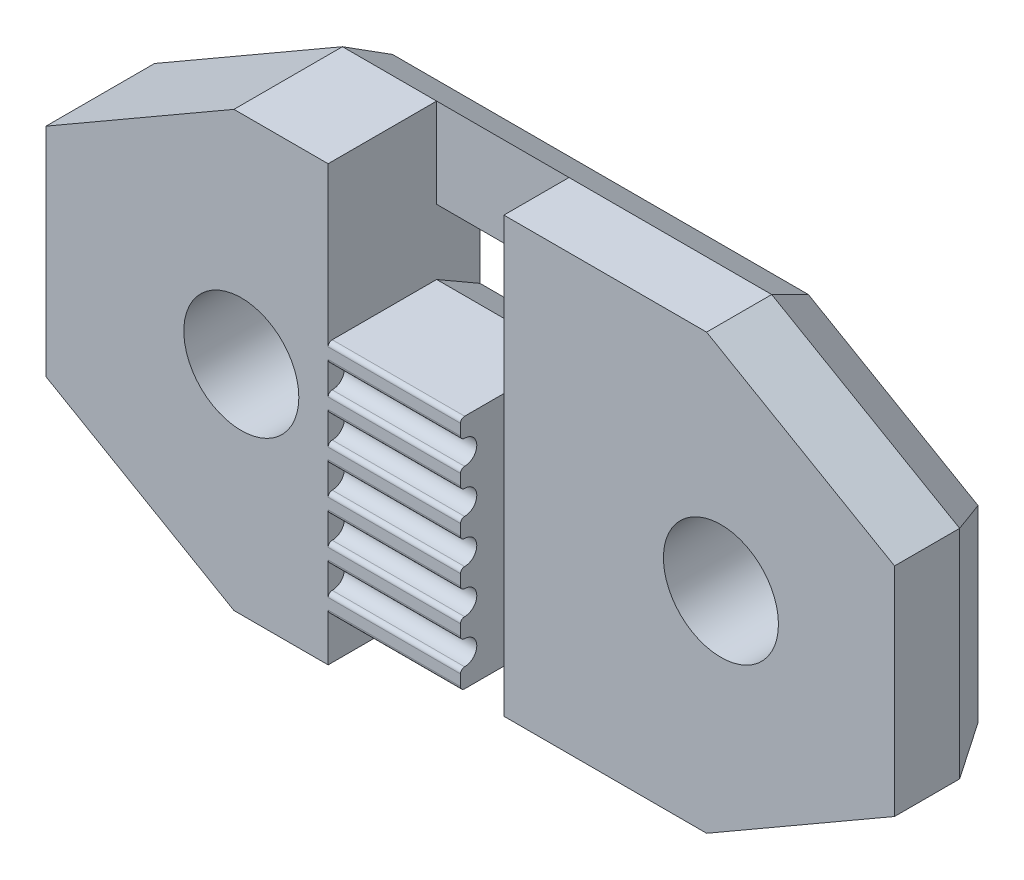
SolidWorks part; units mm, degrees
material "ABS"
ref_plane "Ebene vorne" through (0, 0, 0) normal (0, 0, 1) x (1, 0, 0)
ref_plane "Ebene oben" through (0, 0, 0) normal (0, 1, 0) x (1, 0, 0)
ref_plane "Ebene rechts" through (0, 0, 0) normal (1, 0, 0) x (0, 0, -1)
sketch "Skizze1" plane through (0, 0, 0) normal (0, 0, 1) x (1, 0, 0)
  line L0 (0, 0) -> (0, 9.44)
  line L1 (0, 9.44) -> (-7.24, 9.44) construction
  line L2 (-7.05, 10.19) -> (-7.05, 10.69)
  line L3 (-7.05, 8.69) -> (-7.05, 8.19)
  line L4 (-7.24, 10.88) -> (-9.24, 10.88)
  line L5 (-9.24, 10.88) -> (-9.24, 0)
  line L6 (-7.05, 6.69) -> (-7.05, 6.19)
  line L7 (-7.05, 4.69) -> (-7.05, 4.19)
  line L8 (-7.05, 2.69) -> (-7.05, 2.19)
  line L9 (-7.05, 0.69) -> (-7.05, 0.19)
  line L10 (-7.05, -1.31) -> (-7.05, -1.81) construction
  line L11 (-7.05, -3.31) -> (-7.05, -3.81) construction
  line L12 (-7.05, -5.31) -> (-7.05, -5.81) construction
  line L13 (-7.05, -7.31) -> (-7.05, -7.81) construction
  line L14 (-7.05, -9.31) -> (-7.05, -9.81) construction
  line L15 (-7.24, 0) -> (-9.24, 0)
  line L16 (0, 9.44) -> (0, 10.88)
  line L17 (0, 10.88) -> (-6, 10.88)
  line L18 (-6, 10.88) -> (-6, 0)
  line L19 (-6, 0) -> (0, 0)
  arc A0 (-7.24, 10) -> (-7.24, 8.88) centre (-7.24, 9.44) ccw
  arc A1 (-7.24, 8) -> (-7.24, 6.88) centre (-7.24, 7.44) ccw
  arc A2 (-7.05, 8.69) -> (-7.24, 8.88) centre (-7.24, 8.69) ccw
  arc A3 (-7.24, 8) -> (-7.05, 8.19) centre (-7.24, 8.19) ccw
  arc A4 (-7.05, 10.19) -> (-7.24, 10) centre (-7.24, 10.19) cw
  arc A5 (-7.24, 10.88) -> (-7.05, 10.69) centre (-7.24, 10.69) cw
  arc A6 (-7.24, 8) -> (-7.24, 6.88) centre (-7.24, 7.44) ccw
  arc A7 (-7.05, 6.69) -> (-7.24, 6.88) centre (-7.24, 6.69) ccw
  arc A8 (-7.24, 6) -> (-7.05, 6.19) centre (-7.24, 6.19) ccw
  arc A9 (-7.24, 6) -> (-7.24, 4.88) centre (-7.24, 5.44) ccw
  arc A10 (-7.05, 4.69) -> (-7.24, 4.88) centre (-7.24, 4.69) ccw
  arc A11 (-7.24, 4) -> (-7.05, 4.19) centre (-7.24, 4.19) ccw
  arc A12 (-7.24, 4) -> (-7.24, 2.88) centre (-7.24, 3.44) ccw
  arc A13 (-7.05, 2.69) -> (-7.24, 2.88) centre (-7.24, 2.69) ccw
  arc A14 (-7.24, 2) -> (-7.05, 2.19) centre (-7.24, 2.19) ccw
  arc A15 (-7.24, 2) -> (-7.24, 0.88) centre (-7.24, 1.44) ccw
  arc A16 (-7.05, 0.69) -> (-7.24, 0.88) centre (-7.24, 0.69) ccw
  arc A17 (-7.24, 0) -> (-7.05, 0.19) centre (-7.24, 0.19) ccw
  arc A18 (-7.24, 0) -> (-7.24, -1.12) centre (-7.24, -0.56) ccw construction
  arc A19 (-7.05, -1.31) -> (-7.24, -1.12) centre (-7.24, -1.31) ccw construction
  arc A20 (-7.24, -2) -> (-7.05, -1.81) centre (-7.24, -1.81) ccw construction
  arc A21 (-7.24, -2) -> (-7.24, -3.12) centre (-7.24, -2.56) ccw construction
  arc A22 (-7.05, -3.31) -> (-7.24, -3.12) centre (-7.24, -3.31) ccw construction
  arc A23 (-7.24, -4) -> (-7.05, -3.81) centre (-7.24, -3.81) ccw construction
  arc A24 (-7.24, -4) -> (-7.24, -5.12) centre (-7.24, -4.56) ccw construction
  arc A25 (-7.05, -5.31) -> (-7.24, -5.12) centre (-7.24, -5.31) ccw construction
  arc A26 (-7.24, -6) -> (-7.05, -5.81) centre (-7.24, -5.81) ccw construction
  arc A27 (-7.24, -6) -> (-7.24, -7.12) centre (-7.24, -6.56) ccw construction
  arc A28 (-7.05, -7.31) -> (-7.24, -7.12) centre (-7.24, -7.31) ccw construction
  arc A29 (-7.24, -8) -> (-7.05, -7.81) centre (-7.24, -7.81) ccw construction
  arc A30 (-7.24, -8) -> (-7.24, -9.12) centre (-7.24, -8.56) ccw construction
  arc A31 (-7.05, -9.31) -> (-7.24, -9.12) centre (-7.24, -9.31) ccw construction
  arc A32 (-7.24, -10) -> (-7.05, -9.81) centre (-7.24, -9.81) ccw construction
  point P6 (-7.8, 9.44)
  dimension "D1" = 0.56
  dimension "D3" = 0.75
  dimension "D2" = 2
  dimension "D5" = 2
  dimension "D6" = 1.8
  dimension "D7" = 6
  dimension "D8" = 10.88
  dimension "D4" = 10
extrude "Aufsatz-Linear austragen1" add sketch "Skizze1" along normal blind 6.1
sketch "Skizze2" plane through (0, 0, 6.1) normal (0, 0, 1) x (1, 0, 0)
  line L1 (-6, 10.88) -> (0, 10.88)
  line L2 (-6, 10.88) -> (-6, 0)
  line L3 (-6, 0) -> (0, 0)
  line L4 (0, 10.88) -> (0, 0)
extrude "Schnitt-Linear austragen1" cut sketch "Skizze2" against normal up to surface (6.1 mm away) up to face at (-3, 5.44, 0)
sketch "Skizze3" plane through (-9.24, 0, 0) normal (-1, 0, 0) x (0, 0, 1)
  line L0 (6.1, 0) -> (0, 0) construction
  line L1 (0, -2) -> (-13, -2)
  line L2 (0, -2) -> (0, 18)
  line L3 (0, 18) -> (-13, 18)
  line L4 (-13, -2) -> (-13, 18)
  line L5 (0, 10.88) -> (0, 0) construction
  line L6 (-4, 8) -> (0, 8) construction
  line L7 (6.1, 10.88) -> (6.1, 0) construction
  line L8 (0, 18) -> (6.1, 18)
  line L9 (0, 18) -> (0, 13.88)
  line L10 (0, 13.88) -> (6.1, 13.88)
  line L11 (6.1, 18) -> (6.1, 13.88)
  line L12 (6.1, 10.88) -> (0, 10.88) construction
  circle A0 centre (-4, 8) radius 2.65
  dimension "D4" = 5.3
  dimension "D1" = 20
  dimension "D2" = 2
  dimension "D3" = 4
  dimension "D5" = 13
  dimension "D6" = 3
extrude "Aufsatz-Linear austragen2" add sketch "Skizze3" against normal blind 2.19
sketch "Skizze4" plane through (-9.24, 0, 0) normal (-1, 0, 0) x (0, 0, 1)
  line L1 (6.1, 18) -> (24.1, 18)
  line L2 (6.1, 18) -> (6.1, -2)
  line L3 (6.1, -2) -> (24.1, -2)
  line L4 (24.1, 18) -> (24.1, -2)
  line L10 (6.1, 10.88) -> (0, 10.88)
  line L11 (0, 10.88) -> (0, 13.88)
  line L12 (0, 13.88) -> (6.1, 13.88)
  line L13 (6.1, 13.88) -> (6.1, 18)
  line L14 (6.1, 18) -> (-13, 18)
  line L15 (-13, 18) -> (-13, -2)
  line L16 (-13, -2) -> (0, -2)
  line L17 (0, -2) -> (0, 0)
  line L18 (0, 0) -> (6.1, 0)
  line L19 (6.1, 0) -> (6.1, 10.88)
  line L20 (6.1, 10.88) -> (0, 10.88)
  line L21 (0, 10.88) -> (0, 13.88)
  line L22 (0, 13.88) -> (6.1, 13.88)
  line L23 (6.1, 13.88) -> (6.1, 18)
  line L24 (6.1, 18) -> (-13, 18)
  line L25 (-13, 18) -> (-13, -2)
  line L26 (-13, -2) -> (0, -2)
  line L27 (0, -2) -> (0, 0)
  line L28 (0, 0) -> (6.1, 0)
  line L29 (6.1, 0) -> (6.1, 10.88)
  circle A0 centre (-4, 8) radius 2.65 construction
  circle A1 centre (-4, 8) radius 2.65
  circle A2 centre (16.1, 8) radius 2.65
  line M11 (6.1, 10.88) -> (0, 10.88)
  line M12 (0, 10.88) -> (0, 13.88)
  line M13 (0, 13.88) -> (6.1, 13.88)
  line M14 (6.1, 13.88) -> (6.1, 18)
  line M15 (6.1, 18) -> (-13, 18)
  line M16 (-13, 18) -> (-13, -2)
  line M17 (-13, -2) -> (0, -2)
  line M18 (0, -2) -> (0, 0)
  line M19 (0, 0) -> (6.1, 0)
  line M20 (6.1, 0) -> (6.1, 10.88)
  circle M21 centre (-4, 8) radius 2.65
  dimension "D2" = 10
  dimension "D3" = 8
  dimension "D1" = 0
extrude "Aufsatz-Linear austragen3" add sketch "Skizze4" along normal offset from surface (4.81 mm away) 7 contours L4 L1 L2 L3 A2 M14 M20 | M20 M11 M12 M13 M14 M15 M16 M17 M18 M19 M21 up to face at (-7.05, 6.344, 1.98)
sketch "Skizze5" plane through (-9.24, 0, 0) normal (1, 0, 0) x (0, 0, -1)
  line L7 (-6.1, 13.88) -> (-6.1, 18)
  line L8 (-6.1, 18) -> (-24.1, 18)
  line L9 (-24.1, 18) -> (-24.1, -2)
  line L10 (-24.1, -2) -> (-6.1, -2)
  line L11 (-6.1, -2) -> (-6.1, 0)
  line L12 (-6.1, 0) -> (-6.1, 10.88)
  line L13 (-6.1, 10.88) -> (-6.1, 13.88)
  line L14 (-6.1, 13.88) -> (-6.1, 18)
  line L15 (-6.1, 18) -> (-24.1, 18)
  line L16 (-24.1, 18) -> (-24.1, -2)
  line L17 (-24.1, -2) -> (-6.1, -2)
  line L18 (-6.1, -2) -> (-6.1, 0)
  line L19 (-6.1, 0) -> (-6.1, 10.88)
  line L20 (-6.1, 10.88) -> (-6.1, 13.88)
  circle A0 centre (-16.1, 8) radius 2.65 construction
  circle A1 centre (-16.1, 8) radius 2.65
  dimension "D1" = 0
extrude "Aufsatz-Linear austragen4" add sketch "Skizze5" along normal offset from surface (0.19 mm away) 2 up to face at (-7.05, 6.344, 1.98)
chamfer "Fase1" distance 5 angle 60 4 edges at (-10.55, 18, -13) (-11.55, 18, 24.1) (-11.55, -2, 24.1) (-10.55, -2, -13)
chamfer "Fase2" distance 2 angle 30 11 edges at (-14.05, 10.88, 3.05) (-14.05, 13.88, 3.05) (-14.05, -2, -2.1699) (-14.05, -2, 10.7699) (-14.05, 0.5, 19.7699) (-14.05, 8, 24.1) (-14.05, 15.5, 19.7699) (-14.05, 18, 5.55) (-14.05, 15.5, -8.6699) (-14.05, 8, -13) (-14.05, 0.5, -8.6699)
sketch "Skizze11" plane through (0, -2, 0) normal (0, -1, 0) x (1, 0, 0)
  line L0 (-14.05, 7.6) -> (-14.05, 6.1)
  line L1 (-14.05, 6.1) -> (-14.05, 15.1303) construction
  line L2 (-14.05, 0) -> (-14.05, -1.5)
  line L3 (-12.55, 1.5) -> (-12.55, 4.6)
  line L4 (-11.05, 1.5) -> (-11.05, 4.6)
  arc A0 (-14.05, 6.1) -> (-12.55, 4.6) centre (-14.05, 4.6) cw
  arc A1 (-14.05, 0) -> (-12.55, 1.5) centre (-14.05, 1.5) ccw
  arc A2 (-14.05, -1.5) -> (-11.05, 1.5) centre (-14.05, 1.5) ccw
  arc A3 (-14.05, 7.6) -> (-11.05, 4.6) centre (-14.05, 4.6) cw
  dimension "D1" = 1.5
  dimension "D2" = 1.5
extrude "Schnitt-Linear austragen3" cut sketch "Skizze11" against normal blind 2.5 from offset 4
mirror "Spiegeln1" about plane through (-63.1975, -24.9245, 24.1) normal (0, 0, 1) of bodies 113
delete or keep bodies "Körper-Löschen1" type delete bodies bodies 113
sketch "Skizze12" plane through (0, 18, 0) normal (0, 1, 0) x (1, 0, 0)
  line L0 (-7.24, -48.2) -> (-12.05, -48.2) construction
  line L1 (-7.05, -42.1) -> (-12.05, -42.1)
  line L2 (-7.05, -42.1) -> (-7.05, -48.2)
  line L3 (-7.05, -48.2) -> (-12.05, -48.2)
  line L4 (-12.05, -42.1) -> (-12.05, -48.2)
  line L5 (-14.05, -33.0697) -> (-14.05, -52.2303) construction
  dimension "D1" = 2
  dimension "D2" = 5
extrude "Schnitt-Linear austragen4" cut sketch "Skizze12" against normal up to surface (4.12 mm away)
move or copy body "Körper-Verschieben/Kopieren1" bodies to move or copy 115 copy no rotation origin (-10.55, 0, 42.65) rotation axis (0, -1, 0) rotation angle 90
